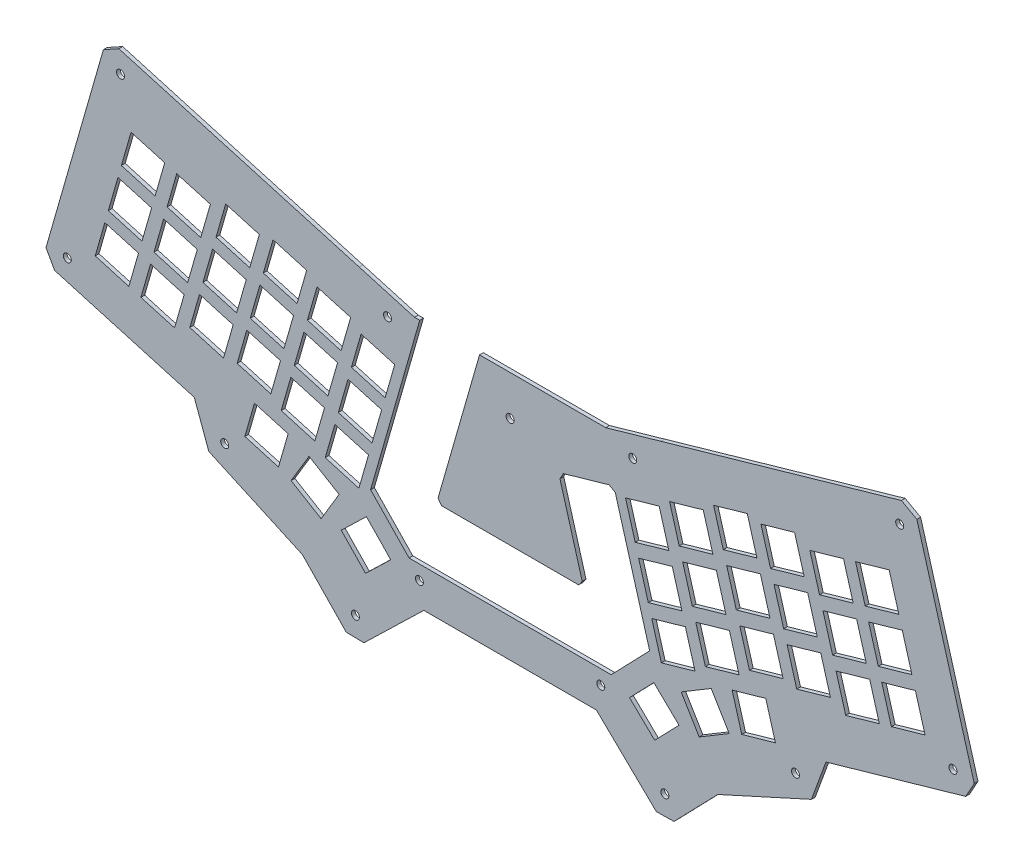
SolidWorks part; units mm, degrees
ref_plane "Plan de face" through (0, 0, 0) normal (0, 0, 1) x (1, 0, 0)
ref_plane "Plan de dessus" through (0, 0, 0) normal (0, 1, 0) x (1, 0, 0)
ref_plane "Plan de droite" through (0, 0, 0) normal (1, 0, 0) x (0, 0, -1)
sketch "Esquisse1" plane through (0, 0, 0) normal (0, 0, 1) x (1, 0, 0)
  line L0 (-121.6461, -32.0475) -> (-108.1875, -28.1884)
  line L1 (-108.1875, -28.1884) -> (-104.3283, -41.647)
  line L2 (-104.3283, -41.647) -> (-117.7869, -45.5062)
  line L3 (-117.7869, -45.5062) -> (-121.6461, -32.0475)
  line L4 (-100.1763, -37.9855) -> (-104.0355, -24.5269)
  line L5 (-104.0355, -24.5269) -> (-90.5769, -20.6677)
  line L6 (-90.5769, -20.6677) -> (-86.7177, -34.1263)
  line L7 (-86.7177, -34.1263) -> (-100.1763, -37.9855)
  line L8 (-82.5657, -30.4649) -> (-86.4249, -17.0063)
  line L9 (-86.4249, -17.0063) -> (-72.9663, -13.1471)
  line L10 (-72.9663, -13.1471) -> (-69.1071, -26.6057)
  line L11 (-69.1071, -26.6057) -> (-82.5657, -30.4649)
  line L12 (-63.6458, -27.5106) -> (-67.505, -14.0519)
  line L13 (-67.505, -14.0519) -> (-54.0463, -10.1927)
  line L14 (-54.0463, -10.1927) -> (-50.1872, -23.6514)
  line L15 (-50.1872, -23.6514) -> (-63.6458, -27.5106)
  line L16 (-44.0711, -26.8394) -> (-47.9303, -13.3808)
  line L17 (-47.9303, -13.3808) -> (-34.4717, -9.5216)
  line L18 (-34.4717, -9.5216) -> (-30.6125, -22.9802)
  line L19 (-30.6125, -22.9802) -> (-44.0711, -26.8394)
  line L20 (-25.8054, -21.6018) -> (-29.6646, -8.1432)
  line L21 (-29.6646, -8.1432) -> (-16.206, -4.284)
  line L22 (-16.206, -4.284) -> (-12.3468, -17.7426)
  line L23 (-12.3468, -17.7426) -> (-25.8054, -21.6018)
  line L24 (-116.4086, -50.3128) -> (-102.95, -46.4536)
  line L25 (-102.95, -46.4536) -> (-99.0908, -59.9122)
  line L26 (-99.0908, -59.9122) -> (-112.5494, -63.7714)
  line L27 (-112.5494, -63.7714) -> (-116.4086, -50.3128)
  line L28 (-98.798, -42.7922) -> (-85.3394, -38.933)
  line L29 (-85.3394, -38.933) -> (-81.4802, -52.3916)
  line L30 (-81.4802, -52.3916) -> (-94.9388, -56.2508)
  line L31 (-94.9388, -56.2508) -> (-98.798, -42.7922)
  line L32 (-81.1874, -35.2715) -> (-67.7288, -31.4123)
  line L33 (-67.7288, -31.4123) -> (-63.8696, -44.8709)
  line L34 (-63.8696, -44.8709) -> (-77.3282, -48.7301)
  line L35 (-77.3282, -48.7301) -> (-81.1874, -35.2715)
  line L36 (-62.2675, -32.3172) -> (-48.8089, -28.458)
  line L37 (-48.8089, -28.458) -> (-44.9497, -41.9166)
  line L38 (-44.9497, -41.9166) -> (-58.4083, -45.7758)
  line L39 (-58.4083, -45.7758) -> (-62.2675, -32.3172)
  line L40 (-42.6928, -31.646) -> (-29.2342, -27.7869)
  line L41 (-29.2342, -27.7869) -> (-25.375, -41.2455)
  line L42 (-25.375, -41.2455) -> (-38.8336, -45.1047)
  line L43 (-38.8336, -45.1047) -> (-42.6928, -31.646)
  line L44 (-24.4271, -26.4084) -> (-10.9685, -22.5492)
  line L45 (-10.9685, -22.5492) -> (-7.1093, -36.0078)
  line L46 (-7.1093, -36.0078) -> (-20.5679, -39.867)
  line L47 (-20.5679, -39.867) -> (-24.4271, -26.4084)
  line L48 (-19.1896, -44.6737) -> (-5.731, -40.8145)
  line L49 (-5.731, -40.8145) -> (-1.8718, -54.2731)
  line L50 (-1.8718, -54.2731) -> (-15.3304, -58.1323)
  line L51 (-15.3304, -58.1323) -> (-19.1896, -44.6737)
  line L52 (-37.4554, -49.9113) -> (-23.9967, -46.0521)
  line L53 (-23.9967, -46.0521) -> (-20.1376, -59.5107)
  line L54 (-20.1376, -59.5107) -> (-33.5962, -63.3699)
  line L55 (-33.5962, -63.3699) -> (-37.4554, -49.9113)
  line L56 (-57.03, -50.5825) -> (-43.5714, -46.7233)
  line L57 (-43.5714, -46.7233) -> (-39.7122, -60.1819)
  line L58 (-39.7122, -60.1819) -> (-53.1708, -64.0411)
  line L59 (-53.1708, -64.0411) -> (-57.03, -50.5825)
  line L60 (-75.9499, -53.5368) -> (-62.4913, -49.6776)
  line L61 (-62.4913, -49.6776) -> (-58.6321, -63.1362)
  line L62 (-58.6321, -63.1362) -> (-72.0908, -66.9954)
  line L63 (-72.0908, -66.9954) -> (-75.9499, -53.5368)
  line L64 (-93.5605, -61.0574) -> (-80.1019, -57.1982)
  line L65 (-80.1019, -57.1982) -> (-76.2427, -70.6569)
  line L66 (-76.2427, -70.6569) -> (-89.7013, -74.516)
  line L67 (-89.7013, -74.516) -> (-93.5605, -61.0574)
  line L68 (-111.1711, -68.5781) -> (-97.7125, -64.7189)
  line L69 (-97.7125, -64.7189) -> (-93.8533, -78.1775)
  line L70 (-93.8533, -78.1775) -> (-107.3119, -82.0367)
  line L71 (-107.3119, -82.0367) -> (-111.1711, -68.5781)
  line L72 (-79.0181, -77.3048) -> (-65.5595, -73.4456)
  line L73 (-65.5595, -73.4456) -> (-61.7003, -86.9042)
  line L74 (-61.7003, -86.9042) -> (-75.1589, -90.7634)
  line L75 (-75.1589, -90.7634) -> (-79.0181, -77.3048)
  line L76 (-99.4001, -88.1351) -> (-87.3916, -80.9362)
  line L77 (-87.3916, -80.9362) -> (-80.1927, -92.9448)
  line L78 (-80.1927, -92.9448) -> (-92.2012, -100.1436)
  line L79 (-92.2012, -100.1436) -> (-99.4001, -88.1351)
  line L80 (-120.0498, -100.4367) -> (-110.317, -90.3719)
  line L81 (-110.317, -90.3719) -> (-100.2522, -100.1047)
  line L82 (-100.2522, -100.1047) -> (-109.985, -110.1695)
  line L83 (-109.985, -110.1695) -> (-120.0498, -100.4367)
  line L86 (0.634, -55.7756) -> (-52.9527, -71.1413) construction
  line L89 (-59.2205, -88.2424) -> (-52.9527, -71.1413) construction
  line L96 (-93.4066, -103.0586) -> (-59.4637, -88.3612) construction
  line L97 (-105.418, -115.2057) -> (-93.9754, -103.3509) construction
  line L98 (-126.5332, -96.9919) -> (-107.5003, -115.385) construction
  line L100 (-106.3822, -25.4572) -> (-123.6848, -30.4187) construction
  line L101 (-72.1178, -10.6906) -> (-88.4663, -15.3784) construction
  line L102 (-53.2337, -7.6163) -> (-70.5393, -12.5786) construction
  line L103 (-33.6604, -6.9452) -> (-50.9661, -11.9075) construction
  line L104 (-15.3965, -1.7081) -> (-31.745, -6.396) construction
  line L105 (0.5403, -55.2132) -> (-14.6896, -2.0999) construction
  line L106 (-16.199, -60.6113) -> (0.1495, -55.9235) construction
  line L107 (-52.7198, -71.0835) -> (-18.1144, -61.1606) construction
  line L108 (-59.1184, -88.0534) -> (-52.9674, -71.2752) construction
  line L113 (-102.2678, -134.438) -> (-84.7238, -116.3191)
  line L114 (-84.7238, -116.3191) -> (-47.2969, -99.2981)
  line L115 (-47.2969, -99.2981) -> (-41.4917, -83.4594)
  line L116 (14.3812, -67.4381) -> (-41.4917, -83.4594)
  line L117 (17.8093, -61.2536) -> (-5.1371, 18.7701)
  line L122 (-11.3217, 22.1985) -> (-107.4545, -5.3614)
  line L129 (-167.7953, -27.6055) -> (-167.7953, -64.7189) construction
  line L130 (-242.0685, -103.8419) -> (-276.37, -88.2424) construction
  line L131 (-229.5108, -116.8112) -> (-242.0685, -103.8419) construction
  line L138 (-208.9328, -96.8551) -> (-229.5108, -116.8112) construction
  line L139 (-225.5107, -79.6567) -> (-208.9328, -96.8551) construction
  line L140 (-109.3352, -134.5492) -> (-102.2678, -134.438)
  line L142 (-5.1371, 18.7701) -> (-11.3217, 22.1985)
  line L143 (-211.4691, -30.6868) -> (-225.5107, -79.6567) construction
  line L147 (-114.18, -7.2899) -> (-107.4545, -5.3614)
  line L148 (-114.18, -7.2899) -> (-129.5654, -11.7015)
  line L154 (-4.3102, 15.8863) -> (-127.3606, -19.3904) construction
  line L155 (-131.531, -101.8802) -> (-105.9239, -126.7133) construction
  line L156 (-105.9239, -126.7133) -> (-89.4162, -109.6646) construction
  line L157 (-127.3539, -97.573) -> (-106.0575, -118.2258) construction
  line L158 (-106.0575, -118.2258) -> (-92.9354, -104.6737) construction
  line L159 (-92.9354, -104.6737) -> (-58.4256, -88.9794) construction
  line L160 (-58.4256, -88.9794) -> (-52.1886, -71.9625) construction
  line L161 (1.8709, -56.4612) -> (-52.1886, -71.9625) construction
  line L162 (1.8709, -56.4612) -> (-14.1861, -0.4639) construction
  line L163 (-14.1861, -0.4639) -> (-50.7166, -10.9388) construction
  line L164 (-50.7166, -10.9388) -> (-52.026, -6.3725) construction
  line L165 (-52.026, -6.3725) -> (-70.2913, -11.61) construction
  line L166 (-70.2913, -11.61) -> (-70.911, -9.4488) construction
  line L167 (-70.911, -9.4488) -> (-90.1377, -14.9608) construction
  line L168 (-90.1377, -14.9608) -> (-89.5177, -17.1231) construction
  line L169 (-89.5177, -17.1231) -> (-107.783, -22.3606) construction
  line L170 (-107.783, -22.3606) -> (-107.0938, -24.7639) construction
  line L171 (-107.0938, -24.7639) -> (-148.4244, -36.6152) construction
  line L172 (-125.3583, -30.0011) -> (-111.0411, -79.9324) construction
  line L173 (-110.7998, -78.9627) -> (-127.3777, -96.1611) construction
  line L174 (-89.4162, -109.6646) -> (-53.6562, -93.4017) construction
  line L175 (-53.6562, -93.4017) -> (-47.6042, -76.8897) construction
  line L176 (9.2923, -60.5749) -> (-47.6042, -76.8897) construction
  line L177 (9.2923, -60.5749) -> (-12.0005, 13.6817) construction
  line L178 (-229.7336, -25.4495) -> (-211.4691, -30.6868) construction
  line L179 (-229.0444, -23.0462) -> (-229.7336, -25.4495) construction
  line L181 (-247.3097, -17.8087) -> (-229.0444, -23.0462) construction
  line L185 (17.8093, -61.2536) -> (14.3812, -67.4381)
  line L190 (-246.6897, -15.6465) -> (-247.3097, -17.8087) construction
  line L191 (-263.9939, -10.6857) -> (-246.6897, -15.6465) construction
  line L192 (-264.6136, -12.8469) -> (-263.9939, -10.6857) construction
  line L193 (-282.8789, -7.6094) -> (-264.6136, -12.8469) construction
  line L194 (-284.1883, -12.1757) -> (-282.8789, -7.6094) construction
  line L195 (-320.7188, -1.7008) -> (-284.1883, -12.1757) construction
  line L196 (-336.2245, -55.7756) -> (-320.7188, -1.7008) construction
  line L200 (-344.8828, -60.5749) -> (-323.5901, 13.6817) construction
  line L201 (-344.8828, -60.5749) -> (-287.9863, -76.8897) construction
  line L202 (-281.9343, -93.4017) -> (-287.9863, -76.8897) construction
  line L203 (-246.1743, -109.6646) -> (-281.9343, -93.4017) construction
  line L204 (-223.5924, -80.2058) -> (-208.2128, -96.1611)
  line L205 (-210.2322, -30.0011) -> (-224.5494, -79.9324) construction
  line L206 (-228.4967, -24.7639) -> (-210.2322, -30.0011) construction
  line L207 (-227.8075, -22.3606) -> (-228.4967, -24.7639) construction
  line L208 (-246.0728, -17.1231) -> (-227.8075, -22.3606) construction
  line L209 (-245.4528, -14.9608) -> (-246.0728, -17.1231) construction
  line L210 (-264.6796, -9.4488) -> (-245.4528, -14.9608) construction
  line L211 (-265.2993, -11.61) -> (-264.6796, -9.4488) construction
  line L212 (-283.5645, -6.3725) -> (-265.2993, -11.61) construction
  line L213 (-284.8739, -10.9388) -> (-283.5645, -6.3725) construction
  line L217 (0.634, -55.7756) -> (-14.8717, -1.7008) construction
  line L220 (-14.8717, -1.7008) -> (-51.4022, -12.1757) construction
  line L221 (-51.4022, -12.1757) -> (-52.7116, -7.6094) construction
  line L222 (-52.7116, -7.6094) -> (-70.9769, -12.8469) construction
  line L223 (-70.9769, -12.8469) -> (-71.5966, -10.6857) construction
  line L224 (-71.5966, -10.6857) -> (-88.9008, -15.6465) construction
  line L225 (-88.9008, -15.6465) -> (-88.2808, -17.8087) construction
  line L226 (-88.2808, -17.8087) -> (-106.5461, -23.0462) construction
  line L227 (-106.5461, -23.0462) -> (-105.8569, -25.4495) construction
  line L228 (-105.8569, -25.4495) -> (-124.1214, -30.6868) construction
  line L231 (-124.1214, -30.6868) -> (-110.0799, -79.6567) construction
  line L232 (-110.0799, -79.6567) -> (-126.6577, -96.8551) construction
  line L233 (-126.6577, -96.8551) -> (-106.0797, -116.8112) construction
  line L234 (-106.0797, -116.8112) -> (-93.522, -103.8419) construction
  line L235 (-93.522, -103.8419) -> (-59.2205, -88.2424) construction
  line L236 (-321.4044, -0.4639) -> (-284.8739, -10.9388) construction
  line L237 (-337.4614, -56.4612) -> (-321.4044, -0.4639) construction
  line L238 (-337.4614, -56.4612) -> (-283.4019, -71.9625) construction
  line L239 (-277.1649, -88.9794) -> (-283.4019, -71.9625) construction
  line L240 (-242.6551, -104.6737) -> (-277.1649, -88.9794) construction
  line L241 (-229.5331, -118.2258) -> (-242.6551, -104.6737) construction
  line L242 (-208.2366, -97.573) -> (-229.5331, -118.2258) construction
  line L243 (-229.6666, -126.7133) -> (-246.1743, -109.6646) construction
  line L244 (-204.0596, -101.8802) -> (-229.6666, -126.7133) construction
  line L245 (-331.2803, 15.8863) -> (-208.2299, -19.3904) construction
  line L251 (-276.4721, -88.0534) -> (-282.6232, -71.2752) construction
  line L252 (-282.8707, -71.0835) -> (-317.4761, -61.1606) construction
  line L253 (-319.3915, -60.6113) -> (-335.74, -55.9235) construction
  line L254 (-336.1309, -55.2132) -> (-320.9009, -2.0999) construction
  line L255 (-320.194, -1.7081) -> (-303.8455, -6.396) construction
  line L256 (-301.9301, -6.9452) -> (-284.6245, -11.9075) construction
  line L257 (-282.3568, -7.6163) -> (-265.0512, -12.5786) construction
  line L258 (-263.4727, -10.6906) -> (-247.1242, -15.3784) construction
  line L259 (-229.2083, -25.4572) -> (-211.9057, -30.4187) construction
  line L261 (-209.0573, -96.9919) -> (-228.0902, -115.385) construction
  line L262 (-230.1725, -115.2057) -> (-241.6151, -103.3509) construction
  line L263 (-242.1839, -103.0586) -> (-276.1268, -88.3612) construction
  line L264 (-276.37, -88.2424) -> (-282.6379, -71.1413) construction
  line L265 (-336.2245, -55.7756) -> (-282.6379, -71.1413) construction
  line L268 (-353.3998, -61.2536) -> (-349.9717, -67.4381)
  line L274 (-221.4105, -7.2899) -> (-206.0252, -11.7015)
  line L275 (-221.4105, -7.2899) -> (-228.136, -5.3614)
  line L276 (-330.4534, 18.7701) -> (-324.2688, 22.1985)
  line L277 (-226.2553, -134.5492) -> (-233.3227, -134.438)
  line L281 (-324.2688, 22.1985) -> (-228.136, -5.3614)
  line L282 (-353.3998, -61.2536) -> (-330.4534, 18.7701)
  line L283 (-349.9717, -67.4381) -> (-294.0988, -83.4594)
  line L284 (-288.2936, -99.2981) -> (-294.0988, -83.4594)
  line L285 (-250.8667, -116.3191) -> (-288.2936, -99.2981)
  line L286 (-233.3227, -134.438) -> (-250.8667, -116.3191)
  line L288 (-225.6055, -110.1695) -> (-215.5407, -100.4367)
  line L289 (-235.3383, -100.1047) -> (-225.6055, -110.1695)
  line L290 (-225.2735, -90.3719) -> (-235.3383, -100.1047)
  line L291 (-215.5407, -100.4367) -> (-225.2735, -90.3719)
  line L292 (-243.3893, -100.1436) -> (-236.1904, -88.1351)
  line L293 (-255.3978, -92.9448) -> (-243.3893, -100.1436)
  line L294 (-248.1989, -80.9362) -> (-255.3978, -92.9448)
  line L295 (-236.1904, -88.1351) -> (-248.1989, -80.9362)
  line L296 (-260.4316, -90.7634) -> (-256.5724, -77.3048)
  line L297 (-273.8902, -86.9042) -> (-260.4316, -90.7634)
  line L298 (-270.031, -73.4456) -> (-273.8902, -86.9042)
  line L299 (-256.5724, -77.3048) -> (-270.031, -73.4456)
  line L300 (-228.2786, -82.0367) -> (-224.4194, -68.5781)
  line L301 (-241.7372, -78.1775) -> (-228.2786, -82.0367)
  line L302 (-237.878, -64.7189) -> (-241.7372, -78.1775)
  line L303 (-224.4194, -68.5781) -> (-237.878, -64.7189)
  line L304 (-245.8892, -74.516) -> (-242.03, -61.0574)
  line L305 (-259.3478, -70.6569) -> (-245.8892, -74.516)
  line L306 (-255.4886, -57.1982) -> (-259.3478, -70.6569)
  line L307 (-242.03, -61.0574) -> (-255.4886, -57.1982)
  line L308 (-263.4998, -66.9954) -> (-259.6406, -53.5368)
  line L309 (-276.9584, -63.1362) -> (-263.4998, -66.9954)
  line L310 (-273.0992, -49.6776) -> (-276.9584, -63.1362)
  line L311 (-259.6406, -53.5368) -> (-273.0992, -49.6776)
  line L312 (-282.4197, -64.0411) -> (-278.5605, -50.5825)
  line L313 (-295.8783, -60.1819) -> (-282.4197, -64.0411)
  line L314 (-292.0191, -46.7233) -> (-295.8783, -60.1819)
  line L315 (-278.5605, -50.5825) -> (-292.0191, -46.7233)
  line L316 (-301.9944, -63.3699) -> (-298.1352, -49.9113)
  line L317 (-315.453, -59.5107) -> (-301.9944, -63.3699)
  line L318 (-311.5938, -46.0521) -> (-315.453, -59.5107)
  line L319 (-298.1352, -49.9113) -> (-311.5938, -46.0521)
  line L320 (-320.2601, -58.1323) -> (-316.4009, -44.6737)
  line L321 (-333.7187, -54.2731) -> (-320.2601, -58.1323)
  line L322 (-329.8595, -40.8145) -> (-333.7187, -54.2731)
  line L323 (-316.4009, -44.6737) -> (-329.8595, -40.8145)
  line L324 (-315.0226, -39.867) -> (-311.1634, -26.4084)
  line L325 (-328.4812, -36.0078) -> (-315.0226, -39.867)
  line L326 (-324.622, -22.5492) -> (-328.4812, -36.0078)
  line L327 (-311.1634, -26.4084) -> (-324.622, -22.5492)
  line L328 (-296.7569, -45.1047) -> (-292.8977, -31.646)
  line L329 (-310.2155, -41.2455) -> (-296.7569, -45.1047)
  line L330 (-306.3563, -27.7869) -> (-310.2155, -41.2455)
  line L331 (-292.8977, -31.646) -> (-306.3563, -27.7869)
  line L332 (-277.1822, -45.7758) -> (-273.323, -32.3172)
  line L333 (-290.6408, -41.9166) -> (-277.1822, -45.7758)
  line L334 (-286.7817, -28.458) -> (-290.6408, -41.9166)
  line L335 (-273.323, -32.3172) -> (-286.7817, -28.458)
  line L336 (-258.2623, -48.7301) -> (-254.4031, -35.2715)
  line L337 (-271.7209, -44.8709) -> (-258.2623, -48.7301)
  line L338 (-267.8617, -31.4123) -> (-271.7209, -44.8709)
  line L339 (-254.4031, -35.2715) -> (-267.8617, -31.4123)
  line L340 (-240.6517, -56.2508) -> (-236.7925, -42.7922)
  line L341 (-254.1103, -52.3916) -> (-240.6517, -56.2508)
  line L342 (-250.2511, -38.933) -> (-254.1103, -52.3916)
  line L343 (-236.7925, -42.7922) -> (-250.2511, -38.933)
  line L344 (-223.0411, -63.7714) -> (-219.1819, -50.3128)
  line L345 (-236.4997, -59.9122) -> (-223.0411, -63.7714)
  line L346 (-232.6405, -46.4536) -> (-236.4997, -59.9122)
  line L347 (-219.1819, -50.3128) -> (-232.6405, -46.4536)
  line L348 (-323.2438, -17.7426) -> (-309.7851, -21.6018)
  line L349 (-319.3846, -4.284) -> (-323.2438, -17.7426)
  line L350 (-305.926, -8.1432) -> (-319.3846, -4.284)
  line L351 (-309.7851, -21.6018) -> (-305.926, -8.1432)
  line L352 (-304.978, -22.9802) -> (-291.5194, -26.8394)
  line L353 (-301.1188, -9.5216) -> (-304.978, -22.9802)
  line L354 (-287.6602, -13.3808) -> (-301.1188, -9.5216)
  line L355 (-291.5194, -26.8394) -> (-287.6602, -13.3808)
  line L356 (-285.4034, -23.6514) -> (-271.9448, -27.5106)
  line L357 (-281.5442, -10.1927) -> (-285.4034, -23.6514)
  line L358 (-268.0856, -14.0519) -> (-281.5442, -10.1927)
  line L359 (-271.9448, -27.5106) -> (-268.0856, -14.0519)
  line L360 (-266.4834, -26.6057) -> (-253.0248, -30.4649)
  line L361 (-262.6242, -13.1471) -> (-266.4834, -26.6057)
  line L362 (-249.1656, -17.0063) -> (-262.6242, -13.1471)
  line L363 (-253.0248, -30.4649) -> (-249.1656, -17.0063)
  line L364 (-248.8728, -34.1263) -> (-235.4142, -37.9855)
  line L365 (-245.0136, -20.6677) -> (-248.8728, -34.1263)
  line L366 (-231.555, -24.5269) -> (-245.0136, -20.6677)
  line L367 (-235.4142, -37.9855) -> (-231.555, -24.5269)
  line L368 (-217.8036, -45.5062) -> (-213.9444, -32.0475)
  line L369 (-231.2622, -41.647) -> (-217.8036, -45.5062)
  line L370 (-227.4031, -28.1884) -> (-231.2622, -41.647)
  line L371 (-213.9444, -32.0475) -> (-227.4031, -28.1884)
  line L372 (-226.2553, -134.5492) -> (-202.2968, -111.3509)
  line L373 (-109.3352, -134.5492) -> (-133.2937, -111.3509)
  line L374 (-141.5559, -103.3509) -> (-194.0347, -103.3509) construction
  line L389 (-206.0252, -11.7015) -> (-129.5654, -11.7015) construction
  line L391 (-223.5924, -80.2058) -> (-203.9491, -11.7015)
  line L394 (-129.5654, -11.7015) -> (-180.0222, -11.7015)
  line L399 (-129.5654, -11.7015) -> (-123.7936, -10.0465) construction
  line L400 (-133.2937, -111.3509) -> (-202.2968, -111.3509)
  line L401 (-141.5559, -111.3509) -> (-194.0347, -111.3509) construction
  line L410 (-192.1766, -64.2267) -> (-167.7953, -64.7189) construction
  line L411 (-196.6354, -69.6386) -> (-180.0222, -11.7015)
  line L412 (-213.9586, -46.6087) -> (-210.0994, -33.1501) construction
  line L413 (-191.8496, -52.9484) -> (-187.9904, -39.4898) construction
  line L414 (-208.2128, -96.1611) -> (-204.2406, -96.1611)
  line L415 (-203.9491, -11.7015) -> (-206.0252, -11.7015)
  line L416 (-127.3777, -96.1611) -> (-131.3499, -96.1611)
  line L417 (-111.9981, -80.2058) -> (-127.3777, -96.1611)
  line L418 (-138.9551, -69.6386) -> (-147.8731, -38.5378)
  line L419 (-111.9981, -80.2058) -> (-125.7641, -32.1981)
  line L420 (-146.5019, -36.064) -> (-128.2379, -30.8269)
  line L421 (-147.8731, -38.5378) -> (-146.5019, -36.064)
  line L422 (-204.2406, -96.1611) -> (-131.3499, -96.1611)
  line L423 (-195.1867, -71.5611) -> (-140.4038, -71.5611)
  line L424 (-196.6354, -69.6386) -> (-195.1867, -71.5611)
  line L425 (-204.2406, -71.5611) -> (-131.3499, -71.5611) construction
  line L426 (-140.4038, -71.5611) -> (-138.9551, -69.6386)
  line L427 (-128.2379, -30.8269) -> (-125.7641, -32.1981)
  circle A2 centre (-12.0005, 13.6817) radius 1.6
  circle A3 centre (-12.0005, 13.6817) radius 3 construction
  circle A4 centre (-118.7579, -16.9241) radius 1.6
  circle A5 centre (9.2923, -60.5749) radius 1.6
  circle A6 centre (-53.6562, -93.4017) radius 1.6
  circle A7 centre (-105.9239, -126.7133) radius 1.6
  circle A8 centre (-131.531, -101.8802) radius 1.6
  circle A10 centre (-147.4897, -45.973) radius 1.6 construction
  circle A11 centre (-323.5901, 13.6817) radius 3 construction
  circle A12 centre (-188.1008, -45.973) radius 1.6 construction
  circle A14 centre (-204.0596, -101.8802) radius 1.6
  circle A15 centre (-229.6666, -126.7133) radius 1.6
  circle A16 centre (-281.9343, -93.4017) radius 1.6
  circle A17 centre (-344.8828, -60.5749) radius 1.6
  circle A18 centre (-216.8326, -16.9241) radius 1.6
  circle A19 centre (-323.5901, 13.6817) radius 1.6
  circle A20 centre (-167.7953, -27.6055) radius 1.6
  point P137 (-126.3154, -30.2756)
  point P138 (-167.7953, -27.6055)
  point P139 (-6.5153, 23.5764)
  point P143 (-197.1867, -71.5611)
  point P150 (-169.1046, -23.0392)
  point P157 (-138.4038, -71.5611)
  point P200 (19.1875, -66.0599)
  point P203 (-141.5228, -71.3355)
  point P204 (-141.5228, 1.5705)
  point P263 (-133.4062, -12.8029)
  point P264 (-118.5195, -64.7189)
  point P283 (-140.1914, -70.9332)
  point P284 (-157.1758, -11.7015)
  point P405 (-354.778, -66.0599)
  point P406 (-329.0752, 23.5764)
  dimension "D3" = 3.2
  dimension "D4" = 6
  dimension "D6" = 3.2
  dimension "D7" = 3.2
  dimension "D8" = 3.2
  dimension "D9" = 3.2
  dimension "D10" = 3.2
  dimension "D16" = 3.2
  dimension "D2" = 4
  dimension "D5" = 8
  dimension "D11" = 23
  dimension "D14" = 24.6
extrude "Boss.-Extru.1" add sketch "Esquisse1" along normal blind 1.5
